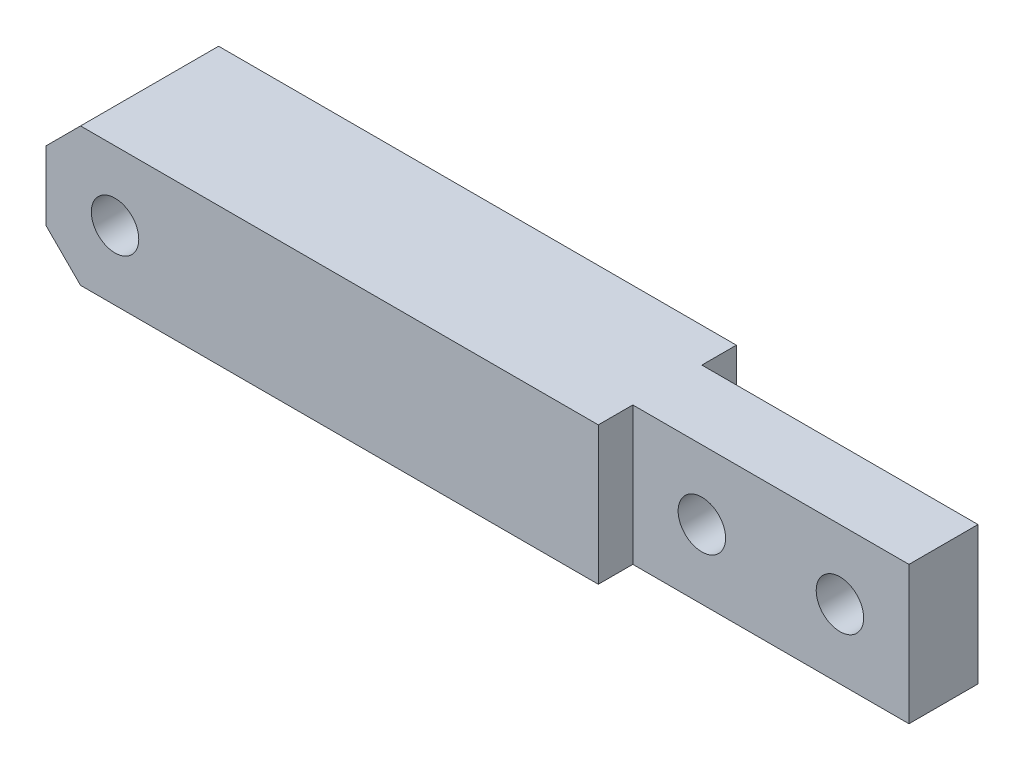
SolidWorks part; units mm, degrees
ref_plane "Front Plane" through (0, 0, 0) normal (0, 0, 1) x (1, 0, 0)
ref_plane "Top Plane" through (0, 0, 0) normal (0, 1, 0) x (1, 0, 0)
ref_plane "Right Plane" through (0, 0, 0) normal (1, 0, 0) x (0, 0, -1)
sketch "Sketch1" plane through (0, 0, 0) normal (0, 1, 0) x (1, 0, 0)
  line L0 (0, 0) -> (50.8, 0)
  line L1 (50.8, 0) -> (50.8, 3.175)
  line L2 (50.8, 3.175) -> (76.2, 3.175)
  line L3 (76.2, 3.175) -> (76.2, 9.525)
  line L4 (76.2, 9.525) -> (50.8, 9.525)
  line L5 (50.8, 9.525) -> (50.8, 12.7)
  line L6 (50.8, 12.7) -> (0, 12.7)
  line L7 (0, 12.7) -> (0, 0)
  point P3 (45.1556, 25.4)
  dimension "D1" = 50.8
  dimension "D2" = 25.4
  dimension "D3" = 3.175
  dimension "D4" = 6.35
  dimension "D5" = 12.7
extrude "Boss-Extrude1" add sketch "Sketch1" along normal mid plane 12.7
sketch "Sketch2" plane through (0, 0, 0) normal (0, 0, 1) x (1, 0, 0)
  circle A0 centre (6.35, 0) radius 2.1828
  circle A1 centre (57.15, 0) radius 2.1828
  circle A2 centre (69.85, 0) radius 2.1828
  dimension "D4" = 4.3656
  dimension "D5" = 4.3656
  dimension "D6" = 4.3656
  dimension "D1" = 6.35
  dimension "D2" = 50.8
  dimension "D3" = 12.7
extrude "Cut-Extrude1" cut sketch "Sketch2" against normal through all both and the other way through all
chamfer "Chamfer1" distance 3.175 angle 45 2 edges at (0, -6.35, -6.35) (0, 6.35, -6.35)
